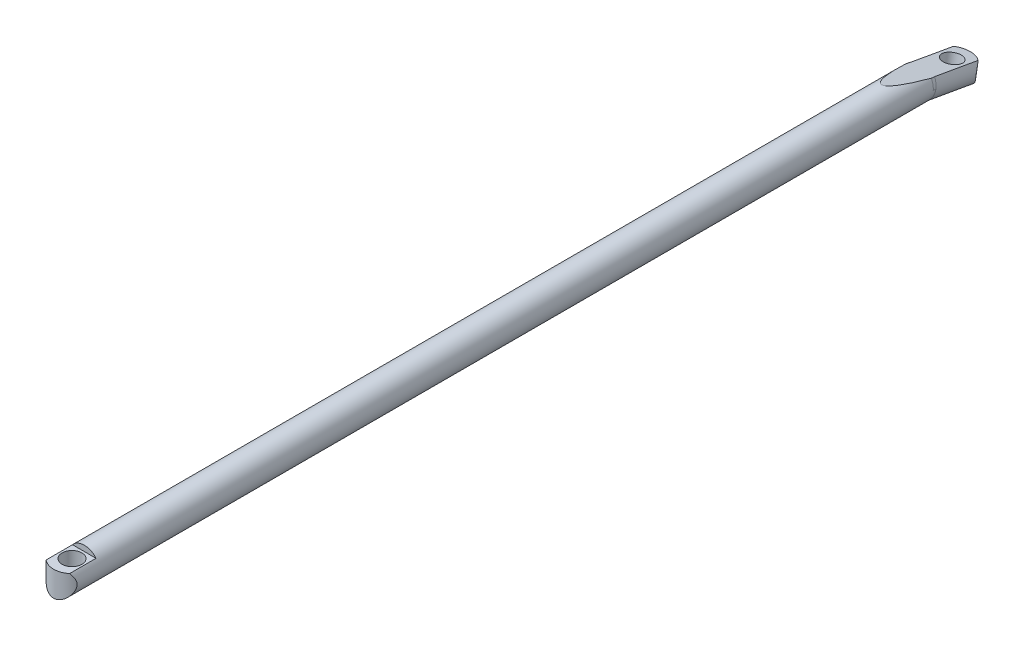
SolidWorks part; units mm, degrees
ref_plane "Front Plane" through (0, 0, 0) normal (0, 0, 1) x (1, 0, 0)
ref_plane "Top Plane" through (0, 0, 0) normal (0, 1, 0) x (1, 0, 0)
ref_plane "Right Plane" through (0, 0, 0) normal (1, 0, 0) x (0, 0, -1)
sketch "Sketch2" plane through (0, 0, 0) normal (0, 0, 1) x (1, 0, 0)
  circle A0 centre (0, 0) radius 12.5
  dimension "D1" = 25
extrude "Boss-Extrude1" add sketch "Sketch2" along normal blind 680
ref_plane "Plane1" through (0, 0, 0) normal (0, 0, -1) x (-1, 0, 0)
sketch "Sketch4" plane through (0, 0, 0) normal (0, 0, -1) x (-1, 0, 0)
  line L1 (0, -12.5) -> (13.9269, -12.5)
  circle A0 centre (0, 0) radius 12.5 construction
ref_plane "Plane2" through (0, -0.3769, -2.1376) normal (0, -0.1736, -0.9848) x (-1, 0, 0)
sketch "Sketch17" plane through (0, -0.3769, -2.1376) normal (0, -0.1736, -0.9848) x (-1, 0, 0)
  circle A0 centre (0, 0) radius 12.5
  dimension "D1" = 25
extrude "Boss-Extrude7" add sketch "Sketch17" against normal up to surface (4.3747 mm away)
sketch "Sketch18" plane through (0, 0, 680) normal (0, 0, 1) x (1, 0, 0)
  circle A0 centre (0, 0) radius 12.5
  circle A1 centre (0, 0) radius 21.642
extrude "Cut-Extrude6" cut sketch "Sketch18" against normal through all
sketch "Sketch19" plane through (0, -0.3769, -2.1376) normal (0, -0.1736, -0.9848) x (-1, 0, 0)
  line L0 (-10, 7.179) -> (10, 7.179)
  arc A0 (-10, 7.179) -> (10, 7.179) centre (0, 0) ccw
  dimension "D2" = 12.3101
  dimension "D1" = 20
extrude "Boss-Extrude8" add sketch "Sketch19" along normal blind 40
sketch "Sketch20" plane through (0, -7.3228, -41.5299) normal (0, -0.1736, -0.9848) x (-1, 0, 0)
  line L0 (-10, 7.179) -> (-31.5339, 7.179)
  line L1 (-31.5339, 7.179) -> (-13.9138, 23.3029)
  line L2 (-13.9138, 23.3029) -> (27.951, 17.3612)
  line L3 (27.951, 17.3612) -> (22.2142, 5.956)
  line L4 (22.2142, 5.956) -> (10, 7.179)
  line L5 (10, 7.179) -> (-10, 7.179)
extrude "Cut-Extrude7" cut sketch "Sketch20" against normal through all
sketch "Sketch21" plane through (0, 7.07, -1.2466) normal (0, 0.9848, -0.1736) x (1, 0, 0)
  line L0 (0, 42.1706) -> (0, 27.1706) construction
  line L1 (-10, 42.1706) -> (10, 42.1706) construction
  line L2 (-15, 27.1706) -> (-29.9093, 27.1706)
  line L3 (-29.9093, 27.1706) -> (-31.2099, 57.2269)
  line L4 (-31.2099, 57.2269) -> (35.1197, 57.2269)
  line L5 (35.1197, 57.2269) -> (27.0375, 28.7999)
  line L6 (27.0375, 28.7999) -> (15, 27.1706)
  circle A0 centre (0, 27.1706) radius 7.5
  arc A1 (15, 27.1706) -> (-15, 27.1706) centre (0, 27.1706) ccw
  dimension "D2" = 15
  dimension "D1" = 15
extrude "Cut-Extrude8" cut sketch "Sketch21" against normal through all
sketch "Sketch23" plane through (0, 0, 680) normal (0, 0, 1) x (1, 0, 0)
  line L0 (-9.6047, 8) -> (9.6047, 8)
  arc A0 (-9.6047, 8) -> (9.6047, 8) centre (0, 0) ccw
  dimension "D1" = 8
extrude "Boss-Extrude9" add sketch "Sketch23" along normal blind 25
sketch "Sketch24" plane through (0, 8, 0) normal (0, 1, 0) x (1, 0, 0)
  line L0 (9.6047, -705) -> (-9.6047, -705) construction
  line L1 (-15, -690) -> (-15, -735.1714)
  line L2 (-15, -735.1714) -> (15, -735.1714)
  line L3 (15, -735.1714) -> (15, -690)
  circle A0 centre (0, -690) radius 8.1016
  arc A1 (-15, -690) -> (15, -690) centre (0, -690) ccw
  dimension "D2" = 30
  dimension "D1" = 15
extrude "Cut-Extrude9" cut sketch "Sketch24" against normal through all
